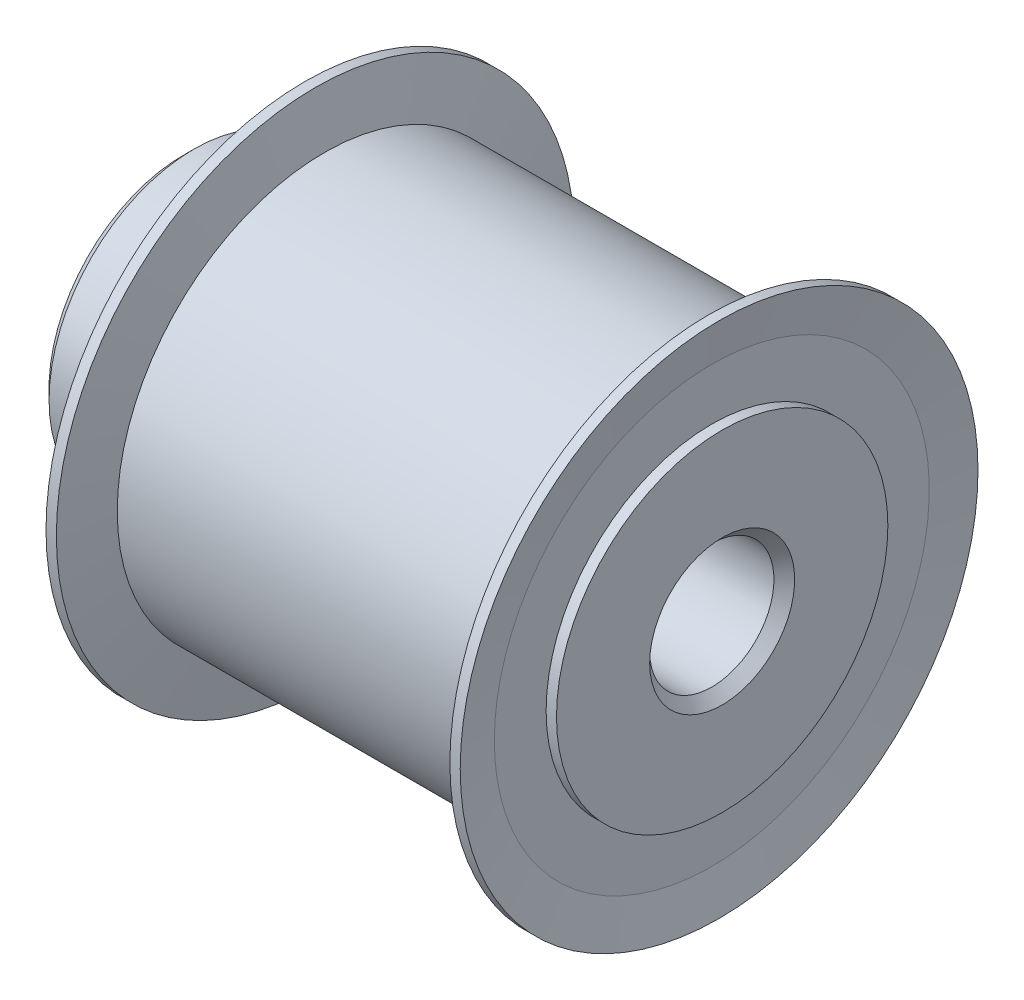
SolidWorks part; units mm, degrees
ref_plane "Ebene vorne" through (0, 0, 0) normal (0, 0, 1) x (1, 0, 0)
ref_plane "Ebene oben" through (0, 0, 0) normal (0, 1, 0) x (1, 0, 0)
ref_plane "Ebene rechts" through (0, 0, 0) normal (1, 0, 0) x (0, 0, -1)
sketch "Skizze1" plane through (0, 0, 0) normal (0, 0, 1) x (1, 0, 0)
  line L0 (0, 0) -> (26, 0) construction
  line L1 (0, 3) -> (26, 3)
  line L2 (0, 3) -> (0, 7)
  line L3 (0, 7) -> (5.7053, 7)
  line L4 (5.7053, 7) -> (5.7053, 8)
  line L5 (5.7053, 8) -> (6.2053, 8)
  line L6 (6.2053, 8) -> (6.2053, 10.5)
  line L7 (6.2053, 10.5) -> (5.8527, 12.5)
  line L8 (5.8527, 12.5) -> (6.3527, 12.5)
  line L9 (6.3527, 12.5) -> (6.7935, 10)
  line L10 (6.7935, 10) -> (24.9118, 10)
  line L11 (24.9118, 10) -> (25.3527, 12.5)
  line L12 (25.3527, 12.5) -> (25.8527, 12.5)
  line L13 (25.8527, 12.5) -> (25.5, 10.5)
  line L14 (25.5, 10.5) -> (25.5, 8)
  line L15 (25.5, 8) -> (26, 8)
  line L16 (26, 8) -> (26, 3)
  point P4 (18.691, 13.1347)
  point P14 (0, 0)
  point P21 (19.5832, 15.9813)
  point P22 (19.5832, 13.1347)
  point P23 (21, 9.0984)
  point P24 (8.5091, 12.1273)
  point P25 (20.5, 10.6718)
  point P26 (9.9261, 10.5)
  dimension "D1" = 3
  dimension "D2" = 26
  dimension "D3" = 0.5
  dimension "D4" = 10
  dimension "D5" = 10
  dimension "D6" = 0.5
  dimension "D7" = 10
  dimension "D8" = 12.5
  dimension "D9" = 8
  dimension "D10" = 10.5
  dimension "D11" = 20
  dimension "D12" = 7
revolve "Rotation1" add sketch "Skizze1" angle 360 about L0
chamfer "Fase1" distance 0.5 angle 45 3 edges at (26, 0, 3) (0, 0, 3) (0, 0, 7)
